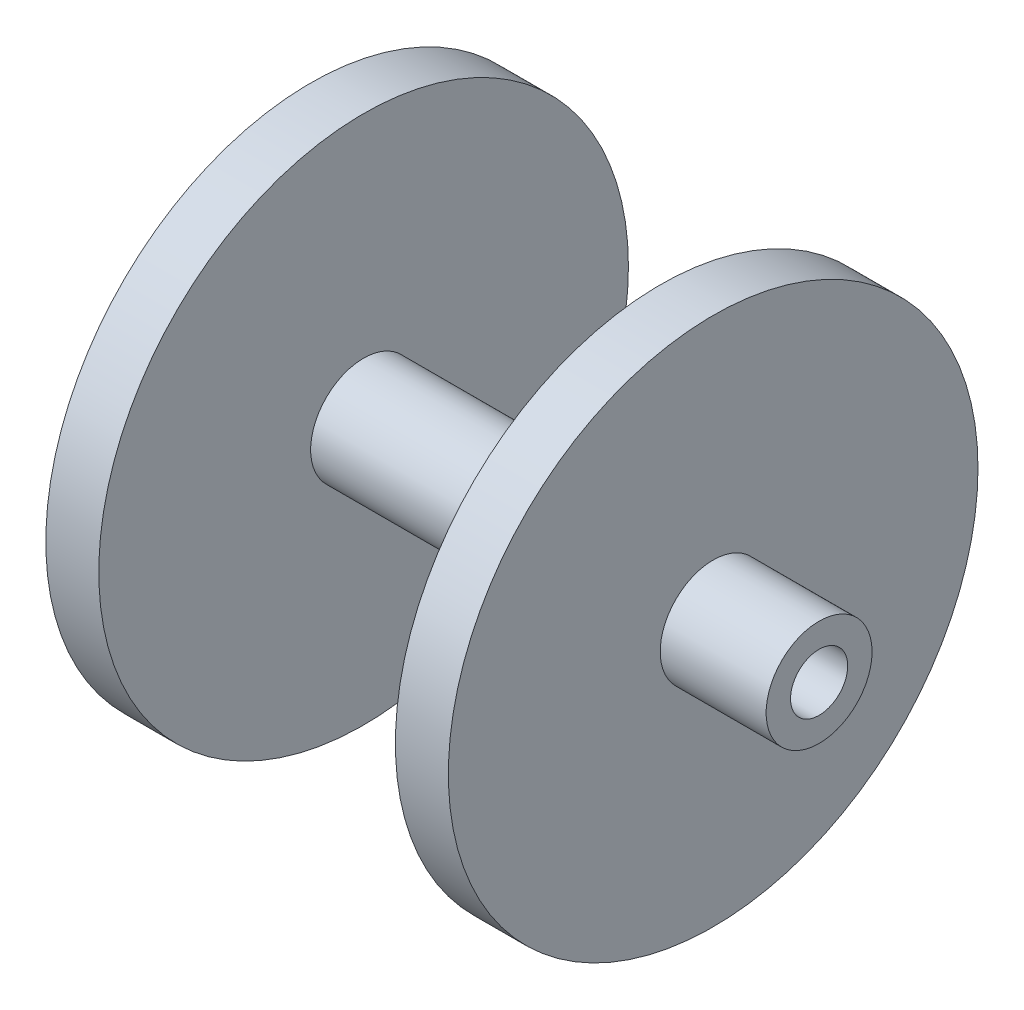
SolidWorks part; units mm, degrees
ref_plane "Front Plane" through (0, 0, 0) normal (0, 0, 1) x (1, 0, 0)
ref_plane "Top Plane" through (0, 0, 0) normal (0, 1, 0) x (1, 0, 0)
ref_plane "Right Plane" through (0, 0, 0) normal (1, 0, 0) x (0, 0, -1)
sketch "Sketch2" plane through (0, 0, 0) normal (0, 0, 1) x (1, 0, 0)
  line L1 (0, 31.75) -> (6.35, 31.75)
  line L2 (6.35, 31.75) -> (6.35, 6.35)
  line L3 (6.35, 6.35) -> (41.91, 6.35)
  line L4 (41.91, 6.35) -> (41.91, 31.75)
  line L5 (41.91, 31.75) -> (48.26, 31.75)
  line L7 (48.26, 0) -> (0, 0)
  line L8 (48.26, 31.75) -> (48.26, 6.35)
  line L9 (48.26, 6.35) -> (60.96, 6.35)
  line L10 (60.96, 6.35) -> (60.96, 0)
  line L11 (60.96, 0) -> (48.26, 0)
  line L12 (0, 31.75) -> (0, 6.35)
  line L13 (0, 6.35) -> (-12.7, 6.35)
  line L14 (-12.7, 6.35) -> (-12.7, 0)
  line L15 (-12.7, 0) -> (0, 0)
  dimension "D1" = 35.56
  dimension "D2" = 6.35
  dimension "D3" = 6.35
  dimension "D4" = 25.4
  dimension "D5" = 0
  dimension "D6" = 6.35
  dimension "D7" = 12.7
  dimension "D8" = 6.35
  dimension "D9" = 12.7
revolve "Revolve1" add sketch "Sketch2" angle 360 about L7
sketch "Sketch4" plane through (60.96, 0, 0) normal (1, 0, 0) x (0, 0, -1)
  circle A0 centre (0, 0) radius 3.429
  dimension "D1" = 6.858
extrude "Cut-Extrude1" cut sketch "Sketch4" against normal blind 5.715
ref_plane "Plane1" through (0, 7.62, 0) normal (0, 1, 0) x (1, 0, 0)
sketch "Sketch5" plane through (0, 7.62, 0) normal (0, 1, 0) x (1, 0, 0)
  line L0 (60.96, -6.35) -> (60.96, 6.35) construction
  point P0 (57.15, 0)
  dimension "D1" = 3.81
equation "\"width_of_film\"= 1.4'a lil more than 35mm"
equation "\"D1@Sketch2\"=\"width_of_film\""
